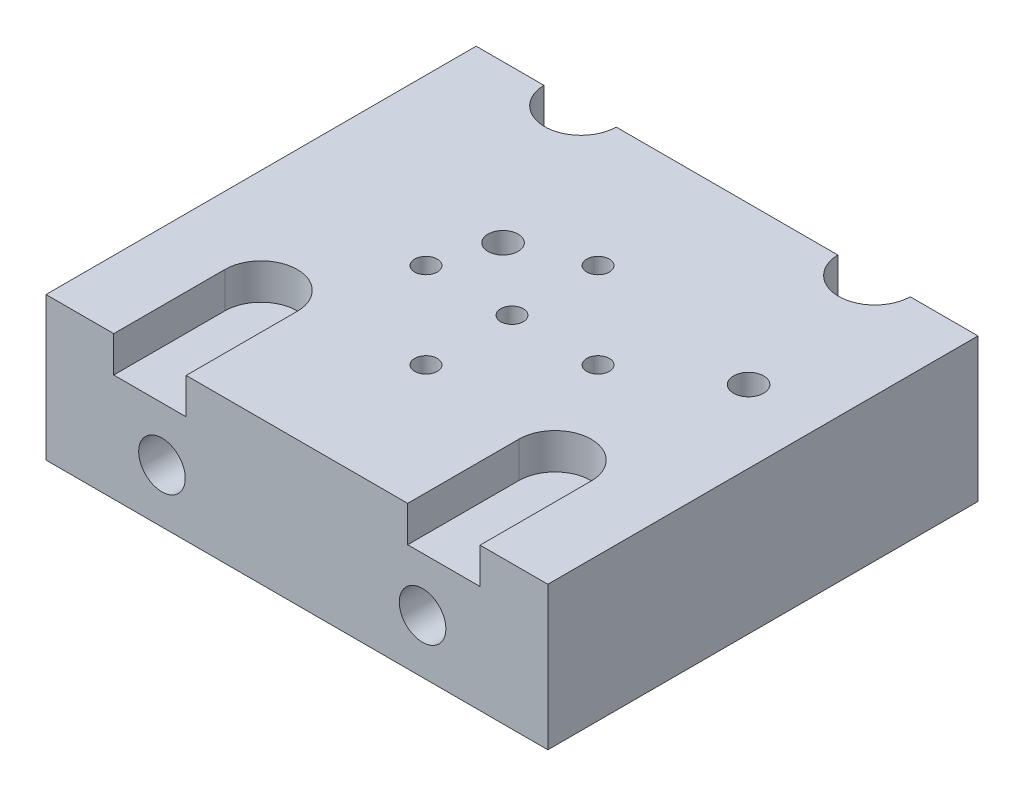
SolidWorks part; units mm, degrees
ref_plane "Front Plane" through (0, 0, 0) normal (0, 0, 1) x (1, 0, 0)
ref_plane "Top Plane" through (0, 0, 0) normal (0, 1, 0) x (1, 0, 0)
ref_plane "Right Plane" through (0, 0, 0) normal (1, 0, 0) x (0, 0, -1)
sketch "Sketch3" plane through (0, 0, 0) normal (0, 1, 0) x (1, 0, 0)
  line L1 (0, 0) -> (70, 0)
  line L2 (0, 0) -> (0, -60)
  line L3 (0, -60) -> (70, -60)
  line L4 (70, 0) -> (70, -60)
  dimension "D1" = 70
  dimension "D2" = 60
extrude "Boss-Extrude3" add sketch "Sketch3" along normal blind 20
sketch "Sketch4" plane through (0, 20, 0) normal (0, 1, 0) x (1, 0, 0)
  line L0 (35, 0) -> (35, -60) construction
  line L1 (70, 0) -> (0, 0) construction
  line L2 (0, -60) -> (70, -60) construction
  line L3 (0, -30) -> (70, -30) construction
  line L4 (0, 0) -> (0, -60) construction
  line L5 (70, -60) -> (70, 0) construction
  line L6 (21.425, -30) -> (21.425, 0) construction
  line L7 (0, 0) -> (70, 0) construction
  line L8 (24.575, -30) -> (24.575, 0) construction
  line L9 (45.425, -30) -> (45.425, 0) construction
  line L10 (48.575, -30) -> (48.575, 0) construction
  circle A0 centre (35, -30) radius 1.575
  circle A1 centre (35, -18) radius 1.575
  circle A2 centre (47, -30) radius 1.575
  circle A3 centre (35, -42) radius 1.575
  circle A4 centre (23, -30) radius 1.575
  dimension "D1" = 3.15
  dimension "D2" = 12
  dimension "D3" = 12
  dimension "D4" = 12
  dimension "D5" = 12
extrude "Cut-Extrude1" cut sketch "Sketch4" against normal through all
sketch "Sketch6" plane through (0, 0, 0) normal (0, -1, 0) x (1, 0, 0)
  line L0 (70, 30) -> (0, 30) construction
  line L1 (51.75, 21.875) -> (33.75, 21.875) construction
  line L2 (68, 21.875) -> (70, 21.875) construction
  line L3 (70, 60) -> (70, 0) construction
  line L4 (0, 0) -> (0, 60) construction
  line L5 (25.625, 21.875) -> (25.625, 0) construction
  line L6 (70, 0) -> (0, 0) construction
  line L7 (59.875, 21.875) -> (59.875, 0) construction
  line L8 (33.75, 21.875) -> (33.75, 0) construction
  line L9 (51.75, 21.875) -> (51.75, 0) construction
  line L10 (17.5, 21.875) -> (17.5, 0) construction
  line L11 (68, 21.875) -> (68, 0) construction
  line L12 (57.775, 21.875) -> (57.775, 0) construction
  line L13 (61.975, 21.875) -> (61.975, 0) construction
  line L14 (27.725, 21.875) -> (27.725, 0) construction
  line L15 (23.525, 21.875) -> (23.525, 0) construction
  line L17 (34.9353, 16.4263) -> (34.9353, 0) construction
  circle A2 centre (59.875, 21.875) radius 8.125 construction
  circle A3 centre (25.625, 21.875) radius 8.125 construction
  circle A4 centre (59.875, 21.875) radius 2.1
  circle A5 centre (25.625, 21.875) radius 2.1
  circle A6 centre (35, 18) radius 1.575 construction
  dimension "D1" = 16.25
  dimension "D2" = 18
  dimension "D3" = 4.2
  dimension "D4" = 2
extrude "Cut-Extrude2" cut sketch "Sketch6" against normal through all contours A4 | A5
sketch "Sketch9" plane through (0, 0, 0) normal (0, 0, -1) x (-1, 0, 0)
  line L0 (-25.625, 0) -> (-25.625, 20) construction
  line L1 (-70, 20) -> (0, 20) construction
  line L2 (-59.875, 0) -> (-59.875, 20) construction
  line L3 (-68, 0) -> (-51.75, 0) construction
  line L4 (-17.5, 0) -> (-17.5, 20) construction
  line L5 (-33.75, 0) -> (-33.75, 20) construction
  line L6 (-51.75, 0) -> (-51.75, 20) construction
  line L7 (-68, 0) -> (-68, 20) construction
  line L8 (-57.775, 0) -> (-57.775, 20) construction
  line L9 (-61.975, 0) -> (-61.975, 20) construction
  line L10 (-27.725, 0) -> (-27.725, 20) construction
  line L11 (-23.525, 0) -> (-23.525, 20) construction
  line L12 (-57.775, 7.5) -> (-55.775, 7.5) construction
  line L13 (-52.525, 10.75) -> (-52.525, 20) construction
  line L14 (-12.925, 7.5) -> (0, 7.5) construction
  line L15 (-19.425, 7.5) -> (-21.425, 7.5) construction
  line L16 (-16.175, 20) -> (-16.175, 10.75) construction
  line L17 (0, 20) -> (0, 0) construction
  line L18 (-34.9353, 0) -> (-34.9353, 20) construction
  line L19 (-34.9353, 0) -> (-34.9353, 20) construction
  line L20 (-49.275, 7.5) -> (-34.9353, 7.5) construction
  line L21 (-21.425, 20) -> (-21.425, 0) construction
  line L22 (0, 0) -> (-70, 0) construction
  line L23 (-24.575, 20) -> (-24.575, 0) construction
  line L24 (-45.425, 20) -> (-45.425, 0) construction
  line L25 (-48.575, 20) -> (-48.575, 0) construction
  line L26 (0, 7.5) -> (0, 20) construction
  circle A0 centre (-52.525, 7.5) radius 3.25
  circle A1 centre (-16.175, 7.5) radius 3.25
  dimension "D1" = 6.5
  dimension "D2" = 2
  dimension "D3" = 2
  dimension "D4" = 12.5
extrude "Cut-Extrude3" cut sketch "Sketch9" against normal through all
sketch "Sketch11" plane through (0, 0, 0) normal (0, -1, 0) x (1, 0, 0)
  line L0 (70, 30) -> (0, 30) construction
  circle A0 centre (23, 30) radius 3
  circle A1 centre (35, 42) radius 3
  circle A2 centre (35, 30) radius 3
  circle A3 centre (35, 18) radius 3
  circle A4 centre (47, 30) radius 3
  circle M3 centre (35, 18) radius 1.575
  circle M4 centre (47, 30) radius 1.575
  circle M5 centre (35, 42) radius 1.575
  circle M6 centre (23, 30) radius 1.575
  circle M7 centre (35, 30) radius 1.575
  dimension "D1" = 6
extrude "Cut-Extrude4" cut sketch "Sketch11" against normal blind 3 contours A3 M3 | A2 M7 | A4 M4 | A0 M6 | A1 M5 | M5 | M6 | M7 | M4 | M3
chamfer "Chamfer1" distance 0.8 angle 45 2 edges at (49.275, 7.5, 0) (12.925, 7.5, 0)
sketch "Sketch12" plane through (0, 20, 0) normal (0, 1, 0) x (1, 0, 0)
  line L0 (35, -60.1049) -> (14.5, -60.1049) construction
  line L1 (35, 0.1049) -> (35, -60.1049) construction
  line L2 (14.5, -60.1049) -> (14.5, -44.5) construction
  line L3 (9.45, -60.1049) -> (9.45, -44.5)
  line L4 (19.55, -60.1049) -> (19.55, -44.5)
  line L5 (70, -30) -> (0, -30) construction
  line L6 (35, 0) -> (35, -60) construction
  line L7 (35, 0.1049) -> (14.5, 0.1049) construction
  line L8 (55.5, -60.1049) -> (55.5, -44.5) construction
  line L9 (60.55, -60.1049) -> (60.55, -44.5)
  line L10 (50.45, -60.1049) -> (50.45, -44.5)
  arc A0 (9.45, -60.1049) -> (19.55, -60.1049) centre (14.5, -60.1049) ccw
  arc A1 (19.55, -44.5) -> (9.45, -44.5) centre (14.5, -44.5) ccw
  circle A2 centre (14.5, 0.1049) radius 5.05
  arc A3 (60.55, -60.1049) -> (50.45, -60.1049) centre (55.5, -60.1049) cw
  arc A4 (50.45, -44.5) -> (60.55, -44.5) centre (55.5, -44.5) cw
  circle A5 centre (55.5, 0.1049) radius 5.05
  point P0 (14.5, -52.3025)
  point P19 (35, -30)
  point P23 (55.5, -52.3025)
  dimension "D4" = 5.05
  dimension "D5" = 10.1
  dimension "D1" = 20.5
extrude "Cut-Extrude5" cut sketch "Sketch12" against normal blind 5
